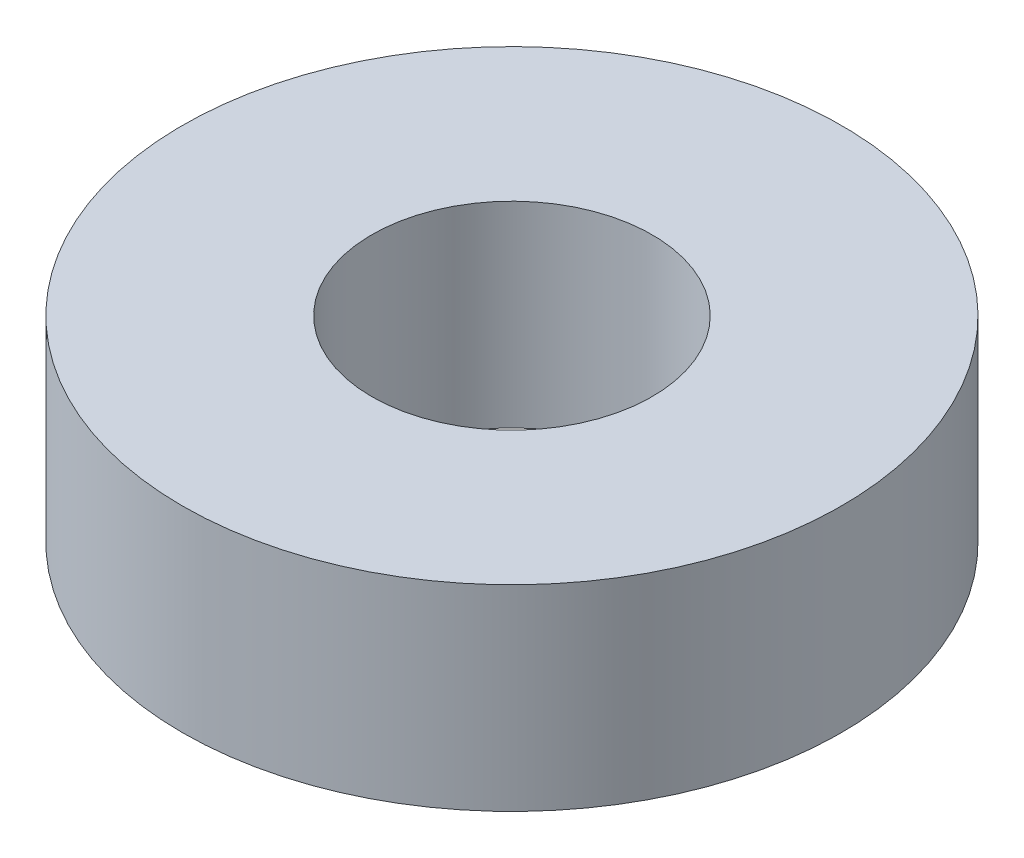
SolidWorks part; units mm, degrees
ref_plane "Front Plane" through (0, 0, 0) normal (0, 0, 1) x (1, 0, 0)
ref_plane "Top Plane" through (0, 0, 0) normal (0, 1, 0) x (1, 0, 0)
ref_plane "Right Plane" through (0, 0, 0) normal (1, 0, 0) x (0, 0, -1)
sketch "Sketch1" plane through (0, 0, 0) normal (0, 1, 0) x (1, 0, 0)
  circle A0 centre (0, 0) radius 10
  circle A1 centre (0, 0) radius 23.5
  dimension "D1" = 47
  dimension "D2" = 20
extrude "Boss-Extrude1" add sketch "Sketch1" along normal blind 14
